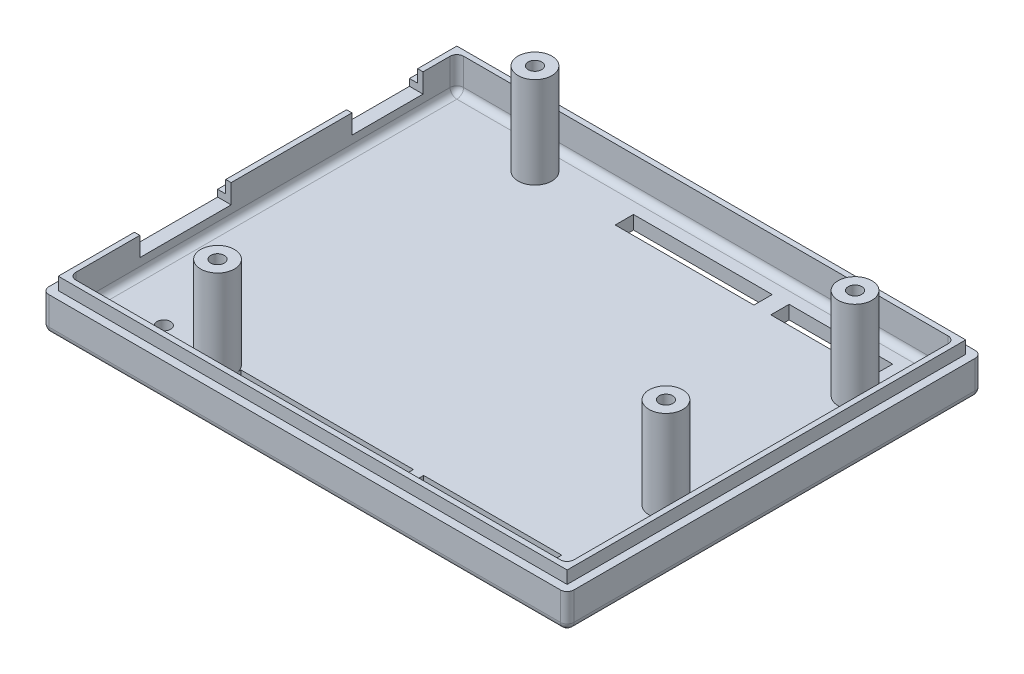
SolidWorks part; units mm, degrees
ref_plane "Front" through (0, 0, 0) normal (0, 0, 1) x (1, 0, 0)
ref_plane "Top" through (0, 0, 0) normal (0, 1, 0) x (1, 0, 0)
ref_plane "Right" through (0, 0, 0) normal (1, 0, 0) x (0, 0, -1)
sketch "Sketch1" plane through (0, 0, 0) normal (0, 1, 0) x (1, 0, 0)
  line L0 (-38.8, 30.65) -> (38.8, -30.65) construction
  line L1 (-38.8, 30.65) -> (38.8, 30.65)
  line L2 (-38.8, 30.65) -> (-38.8, -30.65)
  line L3 (-38.8, -30.65) -> (38.8, -30.65)
  line L4 (38.8, 30.65) -> (38.8, -30.65)
  line L5 (38.8, 30.65) -> (-38.8, -30.65) construction
  point P0 (0, 0)
  dimension "D1" = 61.3
  dimension "D2" = 77.6
extrude "Boss-Extrude1" add sketch "Sketch1" along normal blind 7
sketch "Sketch2" plane through (0, 7, 0) normal (0, 1, 0) x (1, 0, 0)
  line L0 (38.8, 30.65) -> (-38.8, 30.65) construction
  line L1 (-37.6, 29.45) -> (37.6, 29.45)
  line L2 (-37.6, 29.45) -> (-37.6, -29.45)
  line L3 (-37.6, -29.45) -> (37.6, -29.45)
  line L4 (37.6, 29.45) -> (37.6, -29.45)
  line L5 (-38.8, 30.65) -> (-38.8, -30.65) construction
  line L6 (-38.8, -30.65) -> (38.8, -30.65) construction
  line L7 (38.8, -30.65) -> (38.8, 30.65) construction
  dimension "D1" = 1.2
  dimension "D2" = 1.2
  dimension "D3" = 1.2
  dimension "D4" = 1.2
extrude "Cut-Extrude-Thin1" cut sketch "Sketch2" against normal blind 1.85 thin thin type one direction wall 10
sketch "Sketch3" plane through (0, 7, 0) normal (0, 1, 0) x (1, 0, 0)
  line L0 (36.8, 28.65) -> (-36.8, -28.65) construction
  line L1 (-36.8, 28.65) -> (36.8, 28.65)
  line L2 (-36.8, 28.65) -> (-36.8, -28.65)
  line L3 (-36.8, -28.65) -> (36.8, -28.65)
  line L4 (36.8, 28.65) -> (36.8, -28.65)
  line L5 (-36.8, 28.65) -> (36.8, -28.65) construction
  point P0 (0, 0)
  dimension "D1" = 73.6
  dimension "D2" = 57.3
extrude "Cut-Extrude1" cut sketch "Sketch3" against normal blind 5
sketch "Sketch4" plane through (-38.8, 0, 0) normal (-1, 0, 0) x (0, 0, 1)
  line L0 (-29.45, 5.15) -> (29.45, 5.15) construction
  line L1 (18.2, 4.15) -> (4.7, 4.15)
  line L2 (18.2, 4.15) -> (18.2, 7)
  line L3 (18.2, 7) -> (4.7, 7)
  line L4 (4.7, 4.15) -> (4.7, 7)
  line L5 (-13.15, 4.15) -> (-23.65, 4.15)
  line L6 (-13.15, 4.15) -> (-13.15, 7)
  line L7 (-13.15, 7) -> (-23.65, 7)
  line L8 (-23.65, 4.15) -> (-23.65, 7)
  line L9 (-30.65, 5.15) -> (-30.65, 0) construction
  line L10 (30.65, 5.15) -> (30.65, 0) construction
  line L11 (-29.45, 7) -> (29.45, 7) construction
  point P14 (30.65, 2.575)
  dimension "D2" = 1
  dimension "D3" = 13.5
  dimension "D4" = 10.5
  dimension "D5" = 7
  dimension "D6" = 12.45
extrude "Cut-Extrude2" cut sketch "Sketch4" against normal blind 5
fillet "Fillet1" radius 1 16 edges at (0, 0, -30.65) (-38.8, 0, 0) (0, 0, 30.65) (38.8, 0, 0) (0, 2, 28.65) (-36.8, 2, 0) (0, 2, -28.65) (36.8, 2, 0) (-38.8, 2.575, 30.65) (38.8, 2.575, 30.65) (38.8, 2.575, -30.65) (-38.8, 2.575, -30.65) (36.8, 4.5, 28.65) (36.8, 4.5, -28.65) (-36.8, 4.5, -28.65) (-36.8, 4.5, 28.65)
sketch "Sketch5" plane through (0, 2, 0) normal (0, 1, 0) x (1, 0, 0)
  line L1 (30.3, -22.95) -> (9.89, -22.95)
  line L2 (30.3, -22.95) -> (30.3, -25.65)
  line L3 (30.3, -25.65) -> (9.89, -25.65)
  line L4 (9.89, -22.95) -> (9.89, -25.65)
  line L5 (30.3, 23.25) -> (15, 23.25)
  line L6 (30.3, 23.25) -> (30.3, 25.95)
  line L7 (30.3, 25.95) -> (15, 25.95)
  line L8 (15, 23.25) -> (15, 25.95)
  line L9 (12.5, 25.95) -> (-8, 25.95)
  line L10 (12.5, 25.95) -> (12.5, 23.25)
  line L11 (12.5, 23.25) -> (-8, 23.25)
  line L12 (-8, 25.95) -> (-8, 23.25)
  line L13 (-35.8, -28.65) -> (35.8, -28.65) construction
  line L14 (8.39, -22.95) -> (-17.1, -22.95)
  line L15 (8.39, -22.95) -> (8.39, -25.65)
  line L16 (8.39, -25.65) -> (-17.1, -25.65)
  line L17 (-17.1, -22.95) -> (-17.1, -25.65)
  line L18 (35.8, 28.65) -> (-35.8, 28.65) construction
  line L20 (36.8, 27.65) -> (36.8, -27.65) construction
  point P14 (-8, 24.6)
  dimension "D1" = 2.7
  dimension "D2" = 2.7
  dimension "D4" = 2.7
  dimension "D5" = 5.7
  dimension "D6" = 5.4
  dimension "D7" = 6.5
  dimension "D8" = 2.5
  dimension "D9" = 1.5
  dimension "D10" = 15.3
  dimension "D11" = 20.41
  dimension "D3" = 38.3
  dimension "D12" = 47.4
extrude "Cut-Extrude3" cut sketch "Sketch5" against normal up to next
sketch "Sketch6" plane through (0, 2, 0) normal (0, 1, 0) x (1, 0, 0)
  line L7 (36.8, -27.65) -> (36.8, 27.65) construction
  line L9 (35.8, 28.65) -> (-35.8, 28.65) construction
  circle A4 centre (31.6, 19.09) radius 2.5
  circle A5 centre (31.6, -8.85) radius 2.5
  circle A6 centre (-19.5, -24.01) radius 2.5
  circle A7 centre (-20.8, 24.19) radius 2.5
  dimension "D19" = 5
  dimension "D20" = 5
  dimension "D21" = 5
  dimension "D22" = 5
  dimension "D14" = 27.94
  dimension "D15" = 5.2
  dimension "D17" = 52.4
  dimension "D18" = 48.2
  dimension "D16" = 9.56
  dimension "D23" = 5.1
  dimension "D5" = 51.1
extrude "Boss-Extrude2" add sketch "Sketch6" along normal blind 13.5
sketch "Sketch7" plane through (0, 15.5, 0) normal (0, 1, 0) x (1, 0, 0)
  circle A0 centre (31.6, 19.09) radius 1
  circle A1 centre (31.6, -8.85) radius 1
  circle A2 centre (-20.8, 24.19) radius 1
  circle A3 centre (-19.5, -24.01) radius 1
  dimension "D1" = 2
  dimension "D2" = 2
  dimension "D3" = 2
  dimension "D4" = 2
extrude "Cut-Extrude4" cut sketch "Sketch7" against normal blind 5
sketch "Sketch8" plane through (0, 2, 0) normal (0, 1, 0) x (1, 0, 0)
  line L1 (8.39, -22.95) -> (-17.1, -22.95) construction
  circle A0 centre (-28.5, -22.95) radius 1
  circle A1 centre (-19.5, -24.01) radius 2.5 construction
  point P2 (0, 0)
  point P5 (-30.3865, 23.25)
  dimension "D1" = 2
  dimension "D2" = 9
extrude "Cut-Extrude5" cut sketch "Sketch8" against normal up to next
equation "\"D2@Sketch2\"=\"D1@Sketch2\""
equation "\"D3@Sketch2\"=\"D1@Sketch2\""
equation "\"D4@Sketch2\"=\"D1@Sketch2\""
equation "\"D2@Sketch5\"=\"D1@Sketch5\""
equation "\"D4@Sketch5\"=\"D1@Sketch5\""
equation "\"D20@Sketch6\"=\"D19@Sketch6\""
equation "\"D21@Sketch6\"=\"D19@Sketch6\""
equation "\"D22@Sketch6\"=\"D20@Sketch6\""
equation "\"D2@Sketch7\"=\"D1@Sketch7\""
equation "\"D3@Sketch7\"=\"D1@Sketch7\""
equation "\"D4@Sketch7\"=\"D1@Sketch7\""
